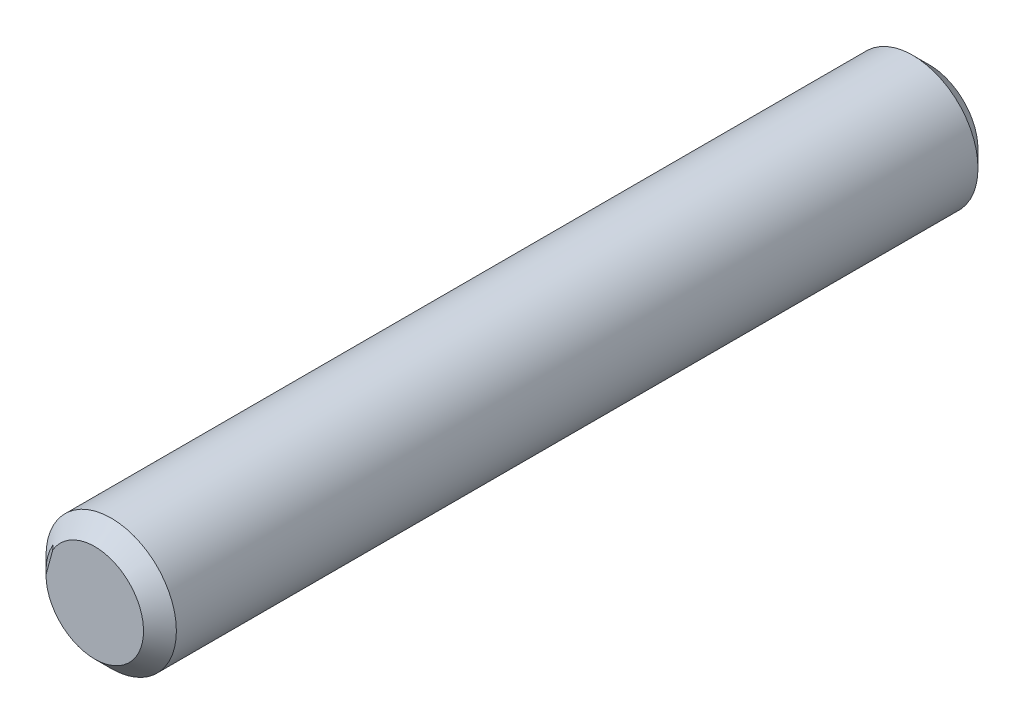
SolidWorks part; units mm, degrees
ref_plane "Front Plane" through (0, 0, 0) normal (0, 0, 1) x (1, 0, 0)
ref_plane "Top Plane" through (0, 0, 0) normal (0, 1, 0) x (1, 0, 0)
ref_plane "Right Plane" through (0, 0, 0) normal (1, 0, 0) x (0, 0, -1)
sketch "Sketch1" plane through (0, 0, 0) normal (0, 0, 1) x (1, 0, 0)
  circle A0 centre (0, 0) radius 1.9844
  dimension "D1" = 3.9688
extrude "Boss-Extrude1" add sketch "Sketch1" along normal mid plane 25.4
chamfer "Chamfer1" distance 0.5 angle 45 2 edges at (1.9844, 0, -12.7) (1.9844, 0, 12.7)
sketch "Sketch2" plane through (0, 0, 12.7) normal (0, 0, 1) x (1, 0, 0)
  line L0 (-1.4844, 0) -> (-1.279, 0.7534)
  line L1 (-1.279, 0.7534) -> (-1.57, 0.8328)
  line L2 (-1.57, 0.8328) -> (-1.7754, 0.0793)
  line L3 (-1.7754, 0.0793) -> (-1.4844, 0)
  line L4 (-1.4844, 0) -> (-1.4809, -0.0038)
  circle A0 centre (0, 0) radius 1.4844 construction
  circle M1 centre (0, 0) radius 1.4844
extrude "Cut-Extrude2" cut sketch "Sketch2" against normal blind 0.1 contours L0 M1 | L2 L3 L1 M1
